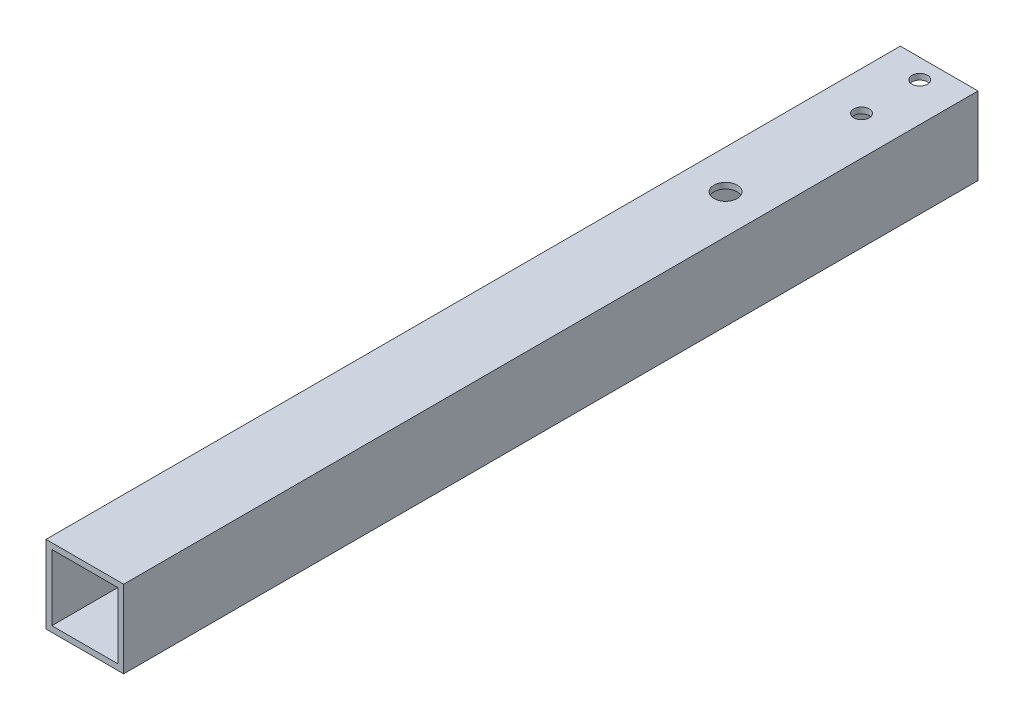
SolidWorks part; units mm, degrees
ref_plane "前视基准面" through (0, 0, 0) normal (0, 0, 1) x (1, 0, 0)
ref_plane "上视基准面" through (0, 0, 0) normal (0, 1, 0) x (1, 0, 0)
ref_plane "右视基准面" through (0, 0, 0) normal (1, 0, 0) x (0, 0, -1)
sketch "草图1" plane through (0, 0, 0) normal (0, 0, 1) x (1, 0, 0)
  line L1 (-10, 10) -> (10, 10)
  line L2 (-10, 10) -> (-10, -10)
  line L3 (-10, -10) -> (10, -10)
  line L4 (10, 10) -> (10, -10)
  line L5 (-10, 10) -> (10, -10) construction
  line L6 (-10, -10) -> (10, 10) construction
  line L7 (-8.5, 8.5) -> (8.5, 8.5)
  line L8 (-8.5, 8.5) -> (-8.5, -8.5)
  line L9 (-8.5, -8.5) -> (8.5, -8.5)
  line L10 (8.5, 8.5) -> (8.5, -8.5)
  line L11 (-8.5, 8.5) -> (8.5, -8.5) construction
  line L12 (-8.5, -8.5) -> (8.5, 8.5) construction
  point P0 (0, 0)
  point P5 (0, 0)
  dimension "D1" = 20
  dimension "D2" = 20
  dimension "D3" = 1.5
  dimension "D4" = 1.5
extrude "凸台-拉伸1" add sketch "草图1" along normal blind 220
sketch "草图3" plane through (0, -10, 0) normal (0, -1, 0) x (1, 0, 0)
  circle A0 centre (0, 20) radius 2
  circle A1 centre (0, 5) radius 2
  dimension "D1" = 4
  dimension "D2" = 5
  dimension "D3" = 15
extrude "切除-拉伸1" cut sketch "草图3" against normal blind 23
sketch "草图4" plane through (0, 10, 0) normal (0, 1, 0) x (1, 0, 0)
  line L0 (10, -220) -> (10, 0) construction
  line L1 (-10, -65) -> (10, -65) construction
  line L2 (-10, -65) -> (-10, -45) construction
  line L3 (-10, -45) -> (10, -45) construction
  line L4 (10, -65) -> (10, -45) construction
  line L5 (-10, -65) -> (10, -45) construction
  line L6 (-10, -45) -> (10, -65) construction
  line L7 (-10, -220) -> (-10, 0) construction
  circle A0 centre (0, -55) radius 3
  point P8 (10, -47.2216)
  point P9 (-10, -45.0037)
  dimension "D1" = 6
  dimension "D2" = 55
extrude "切除-拉伸2" cut sketch "草图4" against normal through all
